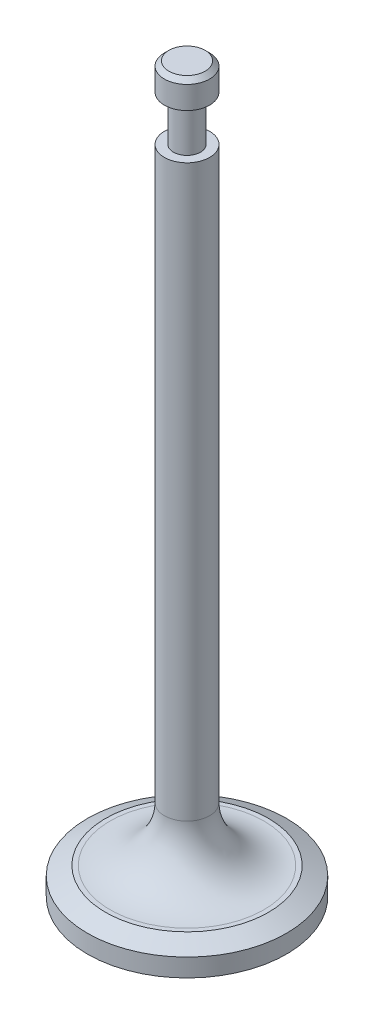
SolidWorks part; units mm, degrees
ref_plane "Ebene vorne" through (0, 0, 0) normal (0, 0, 1) x (1, 0, 0)
ref_plane "Ebene oben" through (0, 0, 0) normal (0, 1, 0) x (1, 0, 0)
ref_plane "Ebene rechts" through (0, 0, 0) normal (1, 0, 0) x (0, 0, -1)
sketch "Sketch1" plane through (0, 0, 0) normal (1, 0, 0) x (0, 0, -1)
  line L0 (0, 0) -> (0, -80)
  line L1 (0, -80) -> (11, -80)
  line L2 (11, -80) -> (11, -77)
  line L3 (11, -77) -> (2.5, -77)
  line L4 (2.5, -77) -> (2.5, -8)
  line L5 (2.5, -8) -> (1.5, -8)
  line L6 (1.5, -8) -> (1.5, -3)
  line L7 (1.5, -3) -> (2.5, -3)
  line L8 (2.5, -3) -> (2.5, 0)
  line L9 (2.5, 0) -> (0, 0)
  dimension "D1" = 11
  dimension "D2" = 80
  dimension "D3" = 3
  dimension "D4" = 2.5
  dimension "D5" = 3
  dimension "D6" = 5
  dimension "D7" = 1
revolve "Revolve1" add sketch "Sketch1" angle 360 about L0
fillet "Fillet1" radius 6 1 edges at (0, -77, 2.5)
chamfer "Chamfer1" distance 1 distance2 2 1 edges at (0, -77, 11)
chamfer "Chamfer2" distance 0.5 angle 45 1 edges at (0, 0, 2.5)
